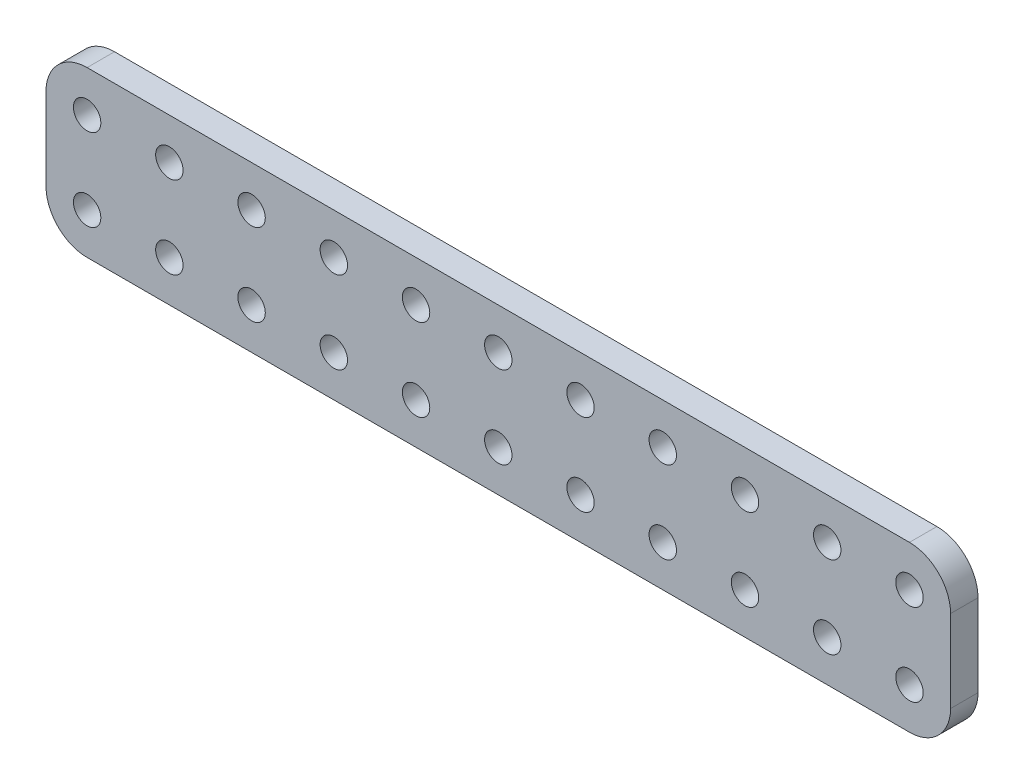
SolidWorks part; units mm, degrees
ref_plane "Alzado" through (0, 0, 0) normal (0, 0, 1) x (1, 0, 0)
ref_plane "Planta" through (0, 0, 0) normal (0, 1, 0) x (1, 0, 0)
ref_plane "Vista lateral" through (0, 0, 0) normal (1, 0, 0) x (0, 0, -1)
sketch "Model" plane through (0, 0, 0) normal (0, 0, 1) x (1, 0, 0)
  line L0 (256.4291, 228.7422) -> (346.4291, 228.7422)
  line L1 (346.4291, 210.7422) -> (256.4291, 210.7422)
  line L2 (350.9291, 224.2422) -> (350.9291, 215.2422)
  line L3 (251.9291, 224.2422) -> (251.9291, 215.2422)
  arc A0 (350.9291, 224.2422) -> (346.4291, 228.7422) centre (346.4291, 224.2422) ccw
  arc A1 (256.4291, 228.7422) -> (251.9291, 224.2422) centre (256.4291, 224.2422) ccw
  arc A2 (251.9291, 215.2422) -> (256.4291, 210.7422) centre (256.4291, 215.2422) ccw
  arc A3 (346.4291, 210.7422) -> (350.9291, 215.2422) centre (346.4291, 215.2422) ccw
  circle A4 centre (310.4291, 224.2422) radius 1.5
  circle A5 centre (292.4291, 224.2422) radius 1.5
  circle A6 centre (301.4291, 224.2422) radius 1.5
  circle A7 centre (337.4291, 215.2422) radius 1.5
  circle A8 centre (319.4291, 215.2422) radius 1.5
  circle A9 centre (328.4291, 215.2422) radius 1.5
  circle A10 centre (310.4291, 215.2422) radius 1.5
  circle A11 centre (292.4291, 215.2422) radius 1.5
  circle A12 centre (301.4291, 215.2422) radius 1.5
  circle A13 centre (274.4291, 215.2422) radius 1.5
  circle A14 centre (283.4291, 215.2422) radius 1.5
  circle A15 centre (265.4291, 215.2422) radius 1.5
  circle A16 centre (256.4291, 215.2422) radius 1.5
  circle A17 centre (346.4291, 215.2422) radius 1.5
  circle A18 centre (274.4291, 224.2422) radius 1.5
  circle A19 centre (265.4291, 224.2422) radius 1.5
  circle A20 centre (256.4291, 224.2422) radius 1.5
  circle A21 centre (283.4291, 224.2422) radius 1.5
  circle A22 centre (337.4291, 224.2422) radius 1.5
  circle A23 centre (319.4291, 224.2422) radius 1.5
  circle A24 centre (328.4291, 224.2422) radius 1.5
  circle A25 centre (346.4291, 224.2422) radius 1.5
extrude "Saliente-Extruir1" add sketch "Model" along normal blind 3
